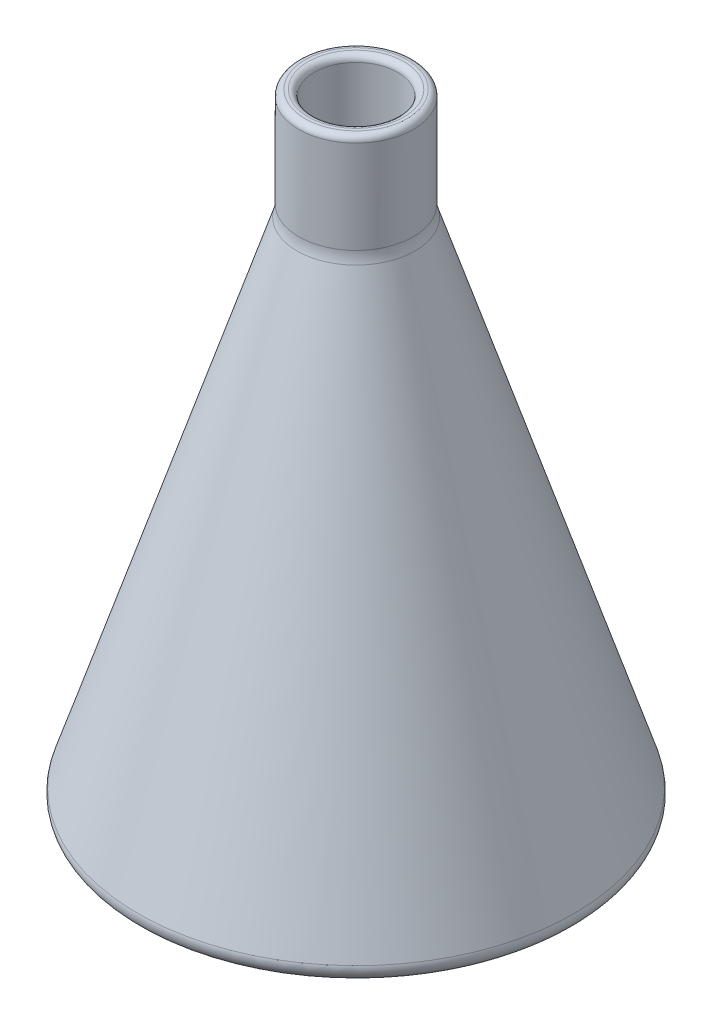
SolidWorks part; units mm, degrees
ref_plane "Front Plane" through (0, 0, 0) normal (0, 0, 1) x (1, 0, 0)
ref_plane "Top Plane" through (0, 0, 0) normal (0, 1, 0) x (1, 0, 0)
ref_plane "Right Plane" through (0, 0, 0) normal (1, 0, 0) x (0, 0, -1)
sketch "Sketch2" plane through (0, 0, 0) normal (0, 0, 1) x (1, 0, 0)
  line L0 (0, 0) -> (0, 127) construction
  line L1 (-11.7045, 127) -> (-8.5295, 127)
  line L2 (-8.5295, 127) -> (-8.5295, 105.5277)
  line L3 (-8.5295, 105.5277) -> (-41.476, 3.175)
  line L4 (-11.7045, 127) -> (-11.7045, 105.5277)
  line L5 (-11.7045, 105.5277) -> (-45.673, 0)
  line L6 (0, 3.175) -> (0, 0)
  line L7 (0, 0) -> (-45.673, 0)
  line L8 (0, 3.175) -> (-41.476, 3.175)
  point P5 (-40.6404, 2.8629)
  point P7 (-45.673, 0.724)
  point P9 (-41.3187, 2.8629)
  dimension "D1" = 127
  dimension "D2" = 3.175
revolve "Revolve1" add sketch "Sketch2" angle 360 about L0
fillet "Fillet1" radius 7.62 1 edges at (0, 105.5277, -11.7045)
fillet "Fillet2" radius 1.27 2 edges at (0, 127, -8.5295) (0, 127, -11.7045)
fillet "Fillet3" radius 2.54 1 edges at (0, 0, -45.673)
fillet "Fillet4" radius 2.54 1 edges at (0, 3.175, -41.476)
sketch "Sketch3" plane through (0, 0, 0) normal (0, 0, 1) x (1, 0, 0)
  line L0 (-42.5786, 9.6131) -> (-42.6918, 9.6496)
  line L1 (-12.071, 104.3891) -> (-44.6049, 3.3183) construction
  line L2 (-42.6918, 9.6496) -> (-41.9136, 12.0674)
  line L3 (-41.9136, 12.0674) -> (-41.8003, 12.0309)
  line L4 (-42.5786, 9.6131) -> (-41.8003, 12.0309)
  line L5 (-38.6872, 21.7023) -> (-38.8005, 21.7387)
  line L6 (-38.8005, 21.7387) -> (-38.0222, 24.1565)
  line L7 (-38.0222, 24.1565) -> (-37.9089, 24.1201)
  line L8 (-38.6872, 21.7023) -> (-37.9089, 24.1201)
  line L9 (-34.7958, 33.7914) -> (-34.9091, 33.8278)
  line L10 (-34.9091, 33.8278) -> (-34.1308, 36.2457)
  line L11 (-34.1308, 36.2457) -> (-34.0175, 36.2092)
  line L12 (-34.7958, 33.7914) -> (-34.0175, 36.2092)
  line L13 (-30.9044, 45.8805) -> (-31.0177, 45.917)
  line L14 (-31.0177, 45.917) -> (-30.2394, 48.3348)
  line L15 (-30.2394, 48.3348) -> (-30.1261, 48.2983)
  line L16 (-30.9044, 45.8805) -> (-30.1261, 48.2983)
  line L17 (-27.013, 57.9696) -> (-27.1263, 58.0061)
  line L18 (-27.1263, 58.0061) -> (-26.348, 60.4239)
  line L19 (-26.348, 60.4239) -> (-26.2348, 60.3875)
  line L20 (-27.013, 57.9696) -> (-26.2348, 60.3875)
  line L21 (-23.1216, 70.0588) -> (-23.2349, 70.0952)
  line L22 (-23.2349, 70.0952) -> (-22.4566, 72.513)
  line L23 (-22.4566, 72.513) -> (-22.3434, 72.4766)
  line L24 (-23.1216, 70.0588) -> (-22.3434, 72.4766)
  line L25 (-19.2302, 82.1479) -> (-19.3435, 82.1844)
  line L26 (-19.3435, 82.1844) -> (-18.5652, 84.6022)
  line L27 (-18.5652, 84.6022) -> (-18.452, 84.5657)
  line L28 (-19.2302, 82.1479) -> (-18.452, 84.5657)
  line L29 (-15.3389, 94.237) -> (-15.4521, 94.2735)
  line L30 (-15.4521, 94.2735) -> (-14.6738, 96.6913)
  line L31 (-14.6738, 96.6913) -> (-14.5606, 96.6549)
  line L32 (-15.3389, 94.237) -> (-14.5606, 96.6549)
  dimension "D1" = 2.54
  dimension "D2" = 8
revolve "Revolve2" add sketch "Sketch3" angle 20 about L0
